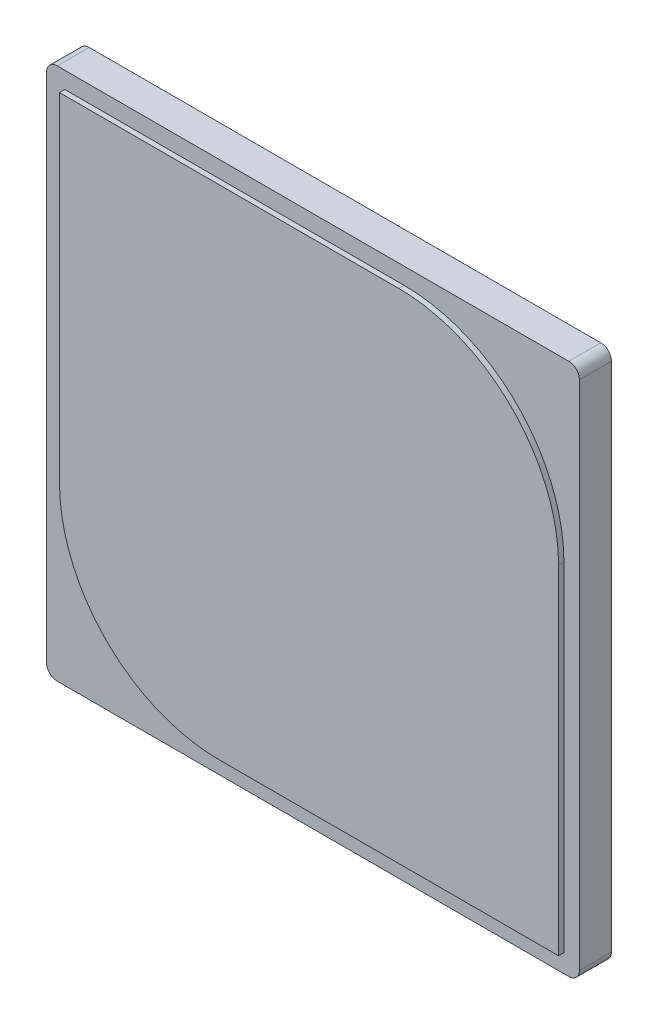
SolidWorks part; units mm, degrees
material "硅"
ref_plane "前视基准面" through (0, 0, 0) normal (0, 0, 1) x (1, 0, 0)
ref_plane "上视基准面" through (0, 0, 0) normal (0, 1, 0) x (1, 0, 0)
ref_plane "右视基准面" through (0, 0, 0) normal (1, 0, 0) x (0, 0, -1)
sketch "草图1" plane through (0, 0, 0) normal (0, 0, 1) x (1, 0, 0)
  line L1 (-15.7317, 17.7317) -> (-5.7317, 17.7317)
  line L2 (-15.7317, 17.7317) -> (-15.7317, 7.7317)
  line L3 (-15.7317, 7.7317) -> (-5.7317, 7.7317)
  line L4 (-5.7317, 17.7317) -> (-5.7317, 7.7317)
  dimension "D1" = 10
  dimension "D2" = 10
extrude "凸台-拉伸1" add sketch "草图1" along normal blind 0.7
sketch "草图2" plane through (0, 0, 0.7) normal (0, 0, 1) x (1, 0, 0)
  line L1 (-15.3896, 17.4198) -> (-9.0235, 17.4198)
  line L2 (-15.3896, 17.4198) -> (-15.3896, 11.0738)
  line L3 (-12.3896, 8.0738) -> (-6.0235, 8.0738)
  line L4 (-6.0235, 14.4198) -> (-6.0235, 8.0738)
  line L5 (-15.7317, 17.7317) -> (-5.7317, 17.7317)
  line L6 (-15.7317, 17.7317) -> (-15.7317, 7.7317)
  line L7 (-15.7317, 7.7317) -> (-5.7317, 7.7317)
  line L8 (-5.7317, 17.7317) -> (-5.7317, 7.7317)
  arc A0 (-6.0235, 14.4198) -> (-9.0235, 17.4198) centre (-9.0235, 14.4198) ccw
  arc A1 (-12.3896, 8.0738) -> (-15.3896, 11.0738) centre (-12.3896, 11.0738) cw
  dimension "D1" = 3
extrude "切除-拉伸1" cut sketch "草图2" against normal blind 0.1
fillet "圆角1" radius 0.2 4 edges at (-15.7317, 7.7317, 0.3) (-5.7317, 7.7317, 0.3) (-5.7317, 17.7317, 0.3) (-15.7317, 17.7317, 0.3)
